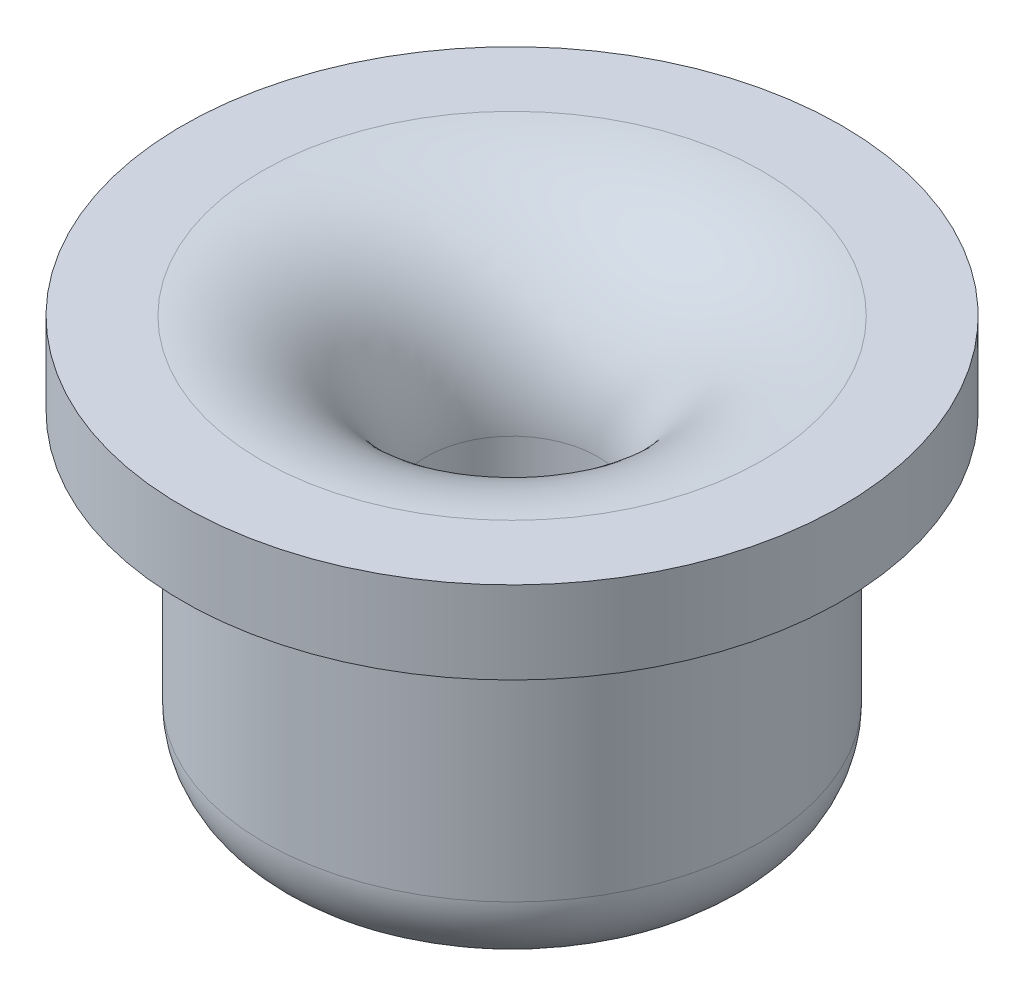
SolidWorks part; units mm, degrees
ref_plane "Front Plane" through (0, 0, 0) normal (0, 0, 1) x (1, 0, 0)
ref_plane "Top Plane" through (0, 0, 0) normal (0, 1, 0) x (1, 0, 0)
ref_plane "Right Plane" through (0, 0, 0) normal (1, 0, 0) x (0, 0, -1)
sketch "Sketch1" plane through (0, 0, 0) normal (1, 0, 0) x (0, 0, -1)
  line L0 (-1.651, 0) -> (-1.651, 7.9375)
  line L1 (-1.651, 7.9375) -> (-6.35, 7.9375)
  line L2 (-6.35, 7.9375) -> (-6.35, 6.35)
  line L3 (-6.35, 6.35) -> (-4.7625, 6.35)
  line L4 (-4.7625, 6.35) -> (-4.7625, 0)
  line L5 (-4.7625, 0) -> (-1.651, 0)
  point P6 (-7.3607, 5.9333)
  point P7 (0, 0)
  dimension "D1" = 1.651
  dimension "D2" = 4.7625
  dimension "D3" = 7.9375
  dimension "D4" = 6.35
  dimension "D5" = 6.35
ref_axis "Axis1" through (0, 0, 0) along (0, 1, 0)
revolve "Revolve1" add sketch "Sketch1" angle 360 about axis through (0, 0, 0) along (0, 1, 0)
fillet "Fillet1" radius 3.175 1 edges at (0, 7.9375, -1.651)
fillet "Fillet4" radius 1.524 2 edges at (0, 0, -4.7625) (0, 0, -1.651)
